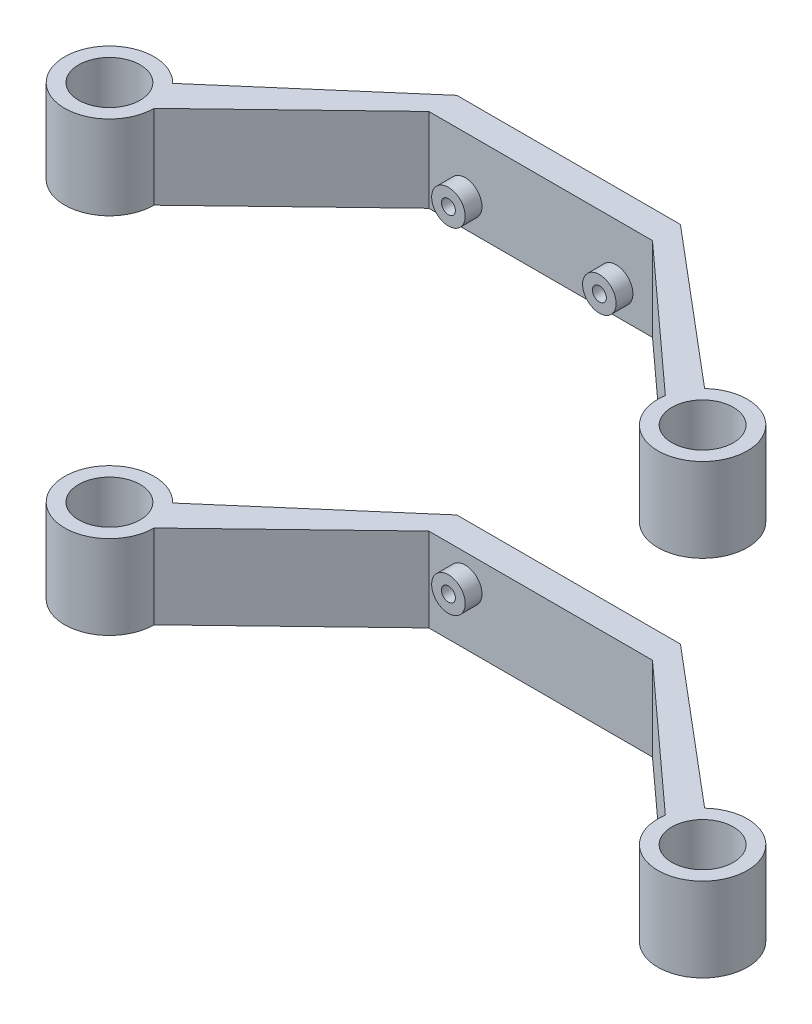
SolidWorks part; units mm, degrees
ref_plane "Front Plane" through (0, 0, 0) normal (0, 0, 1) x (1, 0, 0)
ref_plane "Top Plane" through (0, 0, 0) normal (0, 1, 0) x (1, 0, 0)
ref_plane "Right Plane" through (0, 0, 0) normal (1, 0, 0) x (0, 0, -1)
sketch "Sketch1" plane through (0, 0, 0) normal (0, 0, 1) x (1, 0, 0)
  line L1 (0, 0) -> (40, 0)
  line L2 (0, 0) -> (0, -80)
  line L3 (0, -80) -> (40, -80)
  line L4 (40, 0) -> (40, -80)
  circle A0 centre (6.5, -10) radius 3
  circle A1 centre (33.5, -10) radius 3
  circle A3 centre (6.5, -70) radius 3
  circle A4 centre (33.5, -70) radius 3 [skipped]
  circle A5 centre (6.5, -10) radius 1.25
  circle A6 centre (33.5, -10) radius 1.25
  circle A8 centre (6.5, -70) radius 1.25
  circle A9 centre (33.5, -70) radius 1.25 [skipped]
  dimension "D3" = 6.5
  dimension "D7" = 2
  dimension "D1" = 40
  dimension "D2" = 80
  dimension "D4" = 10
  dimension "D5" = 2
  dimension "D6" = 2
  dimension "D8" = 2
extrude "Boss-Extrude1" add sketch "Sketch1" along normal blind 3 contours L4 L1 L2 L3 A3 A1 A0 | A0 A5 | A1 A6 | A3 A8 | A8
sketch "Sketch2" plane through (0, 0, 3) normal (0, 0, 1) x (1, 0, 0)
  line L4 (40, -80) -> (40, 0)
  line L5 (40, 0) -> (0, 0)
  line L6 (0, 0) -> (0, -80)
  line L7 (0, -80) -> (40, -80)
  line L8 (40, -80) -> (40, 0)
  line L9 (40, 0) -> (0, 0)
  line L10 (0, 0) -> (0, -80)
  line L11 (0, -80) -> (40, -80)
  line L12 (40, 0) -> (0, 0)
  line L13 (40, -80) -> (40, 0)
  line L14 (0, -80) -> (40, -80)
  line L15 (0, 0) -> (0, -80)
  line L16 (40, 0) -> (0, 0)
  line L17 (40, -80) -> (40, 0)
  line L18 (0, -80) -> (40, -80)
  line L19 (0, 0) -> (0, -80)
  circle A1 centre (6.5, -10) radius 1.25
  circle A2 centre (6.5, -10) radius 1.25
  circle A3 centre (6.5, -70) radius 3
  circle A4 centre (6.5, -70) radius 3
  circle A5 centre (33.5, -10) radius 3
  circle A6 centre (33.5, -10) radius 3
  circle A7 centre (6.5, -10) radius 3
  circle A8 centre (6.5, -10) radius 3
  circle A9 centre (6.5, -70) radius 1.25
  circle A10 centre (6.5, -70) radius 1.25
  circle A11 centre (33.5, -10) radius 1.25
  circle A12 centre (33.5, -10) radius 1.25
  dimension "D1" = 0
  dimension "D2" = 0
  dimension "D3" = 0
  dimension "D4" = 0
  dimension "D5" = 0
  dimension "D6" = 0
  dimension "D7" = 0
  dimension "D8" = 0
extrude "Boss-Extrude2" add sketch "Sketch2" along normal blind 5 contours A8 A2 | A6 A12 | A4 A10
sketch "Sketch3" plane through (0, 0, 0) normal (0, 1, 0) x (1, 0, 0)
  line L0 (-27.55, -29.083) -> (67.55, -29.083) construction
  line L2 (20, -82.099) -> (20, 21.1591) construction
  line L4 (0, -3) -> (40, -3) construction
  line L6 (67.5752, -23.2498) -> (40, 0)
  line L7 (40, 0) -> (0, 0)
  line L8 (0, 0) -> (-27.2639, -23.5585)
  line L9 (-25.05, -29.083) -> (0, -5)
  line L10 (40, -5) -> (0, -5)
  line L15 (40, -5) -> (65.1461, -27.8466)
  circle A9 centre (20, -82.099) radius 84.5 construction
  arc A10 (54.3424, -15.4237) -> (-14.3424, -15.4237) centre (20, -82.099) ccw construction
  circle A11 centre (-33.05, -29.083) radius 5.5
  circle A12 centre (73.05, -29.083) radius 5.5
  arc A13 (-27.2639, -23.5585) -> (-25.05, -29.083) centre (-33.05, -29.083) ccw
  arc A14 (65.1461, -27.8466) -> (67.5752, -23.2498) centre (73.05, -29.083) ccw
  arc A15 (-33.05, -29.083) -> (73.05, -29.083) centre (20, -82.099) ccw construction
  dimension "D4" = 40
  dimension "D1" = 169
  dimension "D2" = 150
  dimension "D9" = 11
  dimension "D10" = 11
  dimension "D11" = 8
  dimension "D12" = 8
  dimension "D3" = 106.1
  dimension "D5" = 20
  dimension "D6" = 40
  dimension "D7" = 20
  dimension "D8" = 2
extrude "Boss-Extrude3" add sketch "Sketch3" against normal blind 15
pattern_linear "LPattern1" count 2 spacing 65 along (0, -1, 0) of "Boss-Extrude3"
sketch "Sketch4" plane through (0, 0, 5) normal (0, 0, 1) x (1, 0, 0)
  line L0 (-25.05, -15) -> (0, -15) construction
  line L1 (-7.2392, -15) -> (48.8636, -15)
  line L2 (-7.2392, -15) -> (-7.2392, -65)
  line L3 (-7.2392, -65) -> (48.8636, -65)
  line L4 (48.8636, -15) -> (48.8636, -65)
  line L5 (40, -65) -> (65.1461, -65) construction
extrude "Cut-Extrude1" cut sketch "Sketch4" against normal through all
